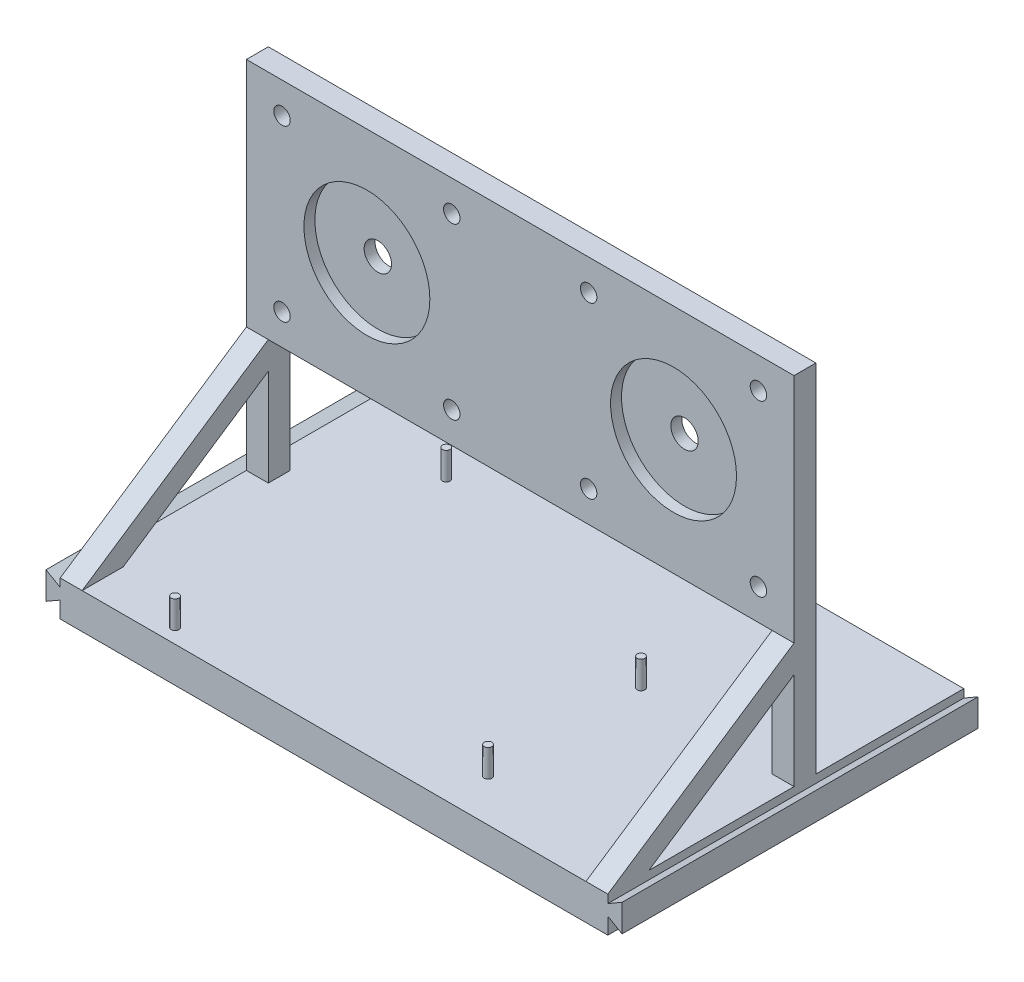
SolidWorks part; units mm, degrees
ref_plane "前视基准面" through (0, 0, 0) normal (0, 0, 1) x (1, 0, 0)
ref_plane "上视基准面" through (0, 0, 0) normal (0, 1, 0) x (1, 0, 0)
ref_plane "右视基准面" through (0, 0, 0) normal (1, 0, 0) x (0, 0, -1)
sketch "草图1" plane through (0, 0, 0) normal (0, 0, 1) x (1, 0, 0)
  line L0 (-50, -30.5) -> (-52.5981, -29)
  line L1 (-55, 35.5) -> (55, 35.5)
  line L2 (-55, 34.0323) -> (-55, -35.5)
  line L3 (-55, -35.5) -> (55, -35.5)
  line L4 (55, 34.0323) -> (55, -35.5)
  line L5 (-55, 35.5) -> (55, -35.5) construction
  line L6 (-55, -35.5) -> (55, 35.5) construction
  line L7 (0, 35.5) -> (0, 85.5) construction
  line L10 (-54.5783, 36.9058) -> (-42.138, 78.3735)
  line L11 (-32.5597, 85.5) -> (0, 85.5)
  line L12 (0, 85.5) -> (32.5597, 85.5)
  line L13 (42.138, 78.3735) -> (54.5783, 36.9058)
  line L14 (-50, -35.5) -> (50, -35.5)
  line L20 (0, 35.5) -> (0, -35.5) construction
  line L23 (-50, 35.5) -> (-38.638, 73.3735)
  line L25 (38.638, 73.3735) -> (50, 35.5)
  line L26 (-50, 35.5) -> (-50, -30.5)
  line L27 (50, 35.5) -> (50, -30.5)
  line L29 (-29.0597, 80.5) -> (0, 80.5)
  line L30 (0, 80.5) -> (29.0597, 80.5)
  line L31 (-52.5981, -29) -> (-52.5981, -34)
  line L32 (-52.5981, -34) -> (-50, -32.5)
  line L33 (50, -30.5) -> (52.5981, -29)
  line L34 (52.5981, -29) -> (52.5981, -34)
  line L35 (52.5981, -34) -> (50, -32.5)
  line L36 (-50, -29) -> (50, -29)
  line L37 (50, -29) -> (50, -30.5)
  line L38 (50, -32.5) -> (50, -35.5)
  line L39 (-50, -35.5) -> (-50, -32.5)
  line L40 (-52.5981, -34) -> (-52.5981, -29)
  line L41 (-50, -32.2727) -> (-50, -35.5)
  line L42 (50, -32.2727) -> (50, -35.5)
  arc A0 (55, 34.0323) -> (54.5783, 36.9058) centre (45, 34.0323) ccw
  arc A1 (42.138, 78.3735) -> (32.5597, 85.5) centre (32.5597, 75.5) ccw
  arc A2 (-32.5597, 85.5) -> (-42.138, 78.3735) centre (-32.5597, 75.5) ccw
  arc A3 (-54.5783, 36.9058) -> (-55, 34.0323) centre (-45, 34.0323) ccw
  arc A4 (38.638, 73.3735) -> (29.0597, 80.5) centre (29.0597, 70.5) ccw
  arc A5 (-29.0597, 80.5) -> (-38.638, 73.3735) centre (-29.0597, 70.5) ccw
  point P0 (0, 0)
  point P25 (40, 85.5)
  point P28 (-40, 85.5)
  dimension "D7" = 10
  dimension "D20" = 10
  dimension "D1" = 110
  dimension "D2" = 5
  dimension "D3" = 50
  dimension "D4" = 40
  dimension "D5" = 71
  dimension "D6" = 40
  dimension "D8" = 120
  dimension "D9" = 120
  dimension "D10" = 5
  dimension "D11" = 1.5
  dimension "D12" = 120
  dimension "D13" = 120
  dimension "D14" = 5
  dimension "D15" = 1.5
  dimension "D16" = 2
  dimension "D17" = 2
  dimension "D18" = 5
  dimension "D19" = 5
extrude "凸台-拉伸7" add sketch "草图1" along normal blind 65
sketch "草图6" plane through (0, -29, 0) normal (0, 1, 0) x (1, 0, 0)
  line L0 (-50, -27) -> (-46, -27)
  line L1 (-50, -27) -> (-50, -31)
  line L2 (-46, -27) -> (-46, -31)
  line L3 (-50, -31) -> (-46, -31)
  line L4 (-50, -65) -> (-50, 0) construction
  line L5 (-50, -65) -> (50, -65) construction
  dimension "D1" = 34
  dimension "D2" = 4
  dimension "D3" = 4
extrude "凸台-拉伸10" add sketch "草图6" along normal blind 65
mirror "镜向1" about plane through (0, 0, 0) normal (1, 0, 0) of "凸台-拉伸10"
sketch "草图7" plane through (-46, 0, 0) normal (1, 0, 0) x (0, 0, -1)
  line L0 (-31, 36) -> (-27, 36)
  line L1 (-31, 36) -> (-31, -6.3)
  line L2 (-27, 36) -> (-27, -6.3)
  line L3 (-31, -6.3) -> (-27, -6.3)
  dimension "D1" = 42.3
extrude "凸台-拉伸11" add sketch "草图7" along normal blind 92
sketch "草图8" plane through (0, 0, 31) normal (0, 0, 1) x (1, 0, 0)
  line L0 (0, 36) -> (0, -6.3) construction
  line L1 (-50, 36) -> (50, 36) construction
  line L2 (46, -6.3) -> (-46, -6.3) construction
  circle A0 centre (-28, 14.85) radius 11.5
  circle A1 centre (28, 14.85) radius 11.5
  dimension "D1" = 23
  dimension "D2" = 21.15
  dimension "D3" = 56
extrude "切除-拉伸2" cut sketch "草图8" against normal blind 2
sketch "草图10" plane through (0, 0, 29) normal (0, 0, 1) x (1, 0, 0)
  line L0 (0, 36) -> (0, -6.3) construction
  line L1 (-50, 36) -> (50, 36) construction
  line L2 (46, -6.3) -> (-46, -6.3) construction
  circle A0 centre (-28, 14.85) radius 2.5
  circle A1 centre (28, 14.85) radius 2.5
  dimension "D1" = 5
  dimension "D2" = 56
  dimension "D3" = 21.15
extrude "切除-拉伸3" cut sketch "草图10" against normal blind 2
sketch "草图11" plane through (0, 0, 31) normal (0, 0, 1) x (1, 0, 0)
  line L4 (-50, 36) -> (50, 36) construction
  line L5 (46, -6.3) -> (-46, -6.3) construction
  line L7 (0, 36) -> (0, -6.3) construction
  circle A0 centre (-43.5, 30.35) radius 1.5
  circle A1 centre (-12.5, 30.35) radius 1.5
  circle A2 centre (-43.5, -0.65) radius 1.5
  circle A3 centre (-12.5, -0.65) radius 1.5
  circle A4 centre (12.5, 30.35) radius 1.5
  circle A5 centre (43.5, 30.35) radius 1.5
  circle A6 centre (12.5, -0.65) radius 1.5
  circle A7 centre (43.5, -0.65) radius 1.5
  dimension "D3" = 3
extrude "切除-拉伸6" cut sketch "草图11" against normal blind 4
ref_plane "基准面1" through (48, 0, 0) normal (1, 0, 0) x (0, 0, -1)
sketch "草图13" plane through (48, 0, 0) normal (1, 0, 0) x (0, 0, -1)
  line L0 (-65, -29) -> (-31, -6.3)
  line L1 (-31, -6.3) -> (-31, -11.3)
  line L2 (-31, 36) -> (-31, -29) construction
  line L3 (-31, -11.3) -> (-57.511, -29)
  line L4 (-65, -29) -> (0, -29) construction
  line L5 (-65, -29) -> (-57.511, -29)
  dimension "D1" = 5
extrude "凸台-拉伸13" add sketch "草图13" along normal blind 2 and the other way blind 2
mirror "镜向3" about plane through (0, 0, 0) normal (1, 0, 0) of "凸台-拉伸13"
sketch "草图14" plane through (0, -29, 0) normal (0, 1, 0) x (1, 0, 0)
  circle A0 centre (-30.4075, -14.0904) radius 0.7
  circle A1 centre (-31.6775, -62.3504) radius 0.7
  circle A2 centre (20.3925, -29.3304) radius 0.7
  circle A3 centre (20.3925, -57.2704) radius 0.7
  dimension "D3" = 1.4
  dimension "D4" = 1.4
  dimension "D5" = 1.4
  dimension "D6" = 1.4
extrude "凸台-拉伸14" add sketch "草图14" along normal blind 5
